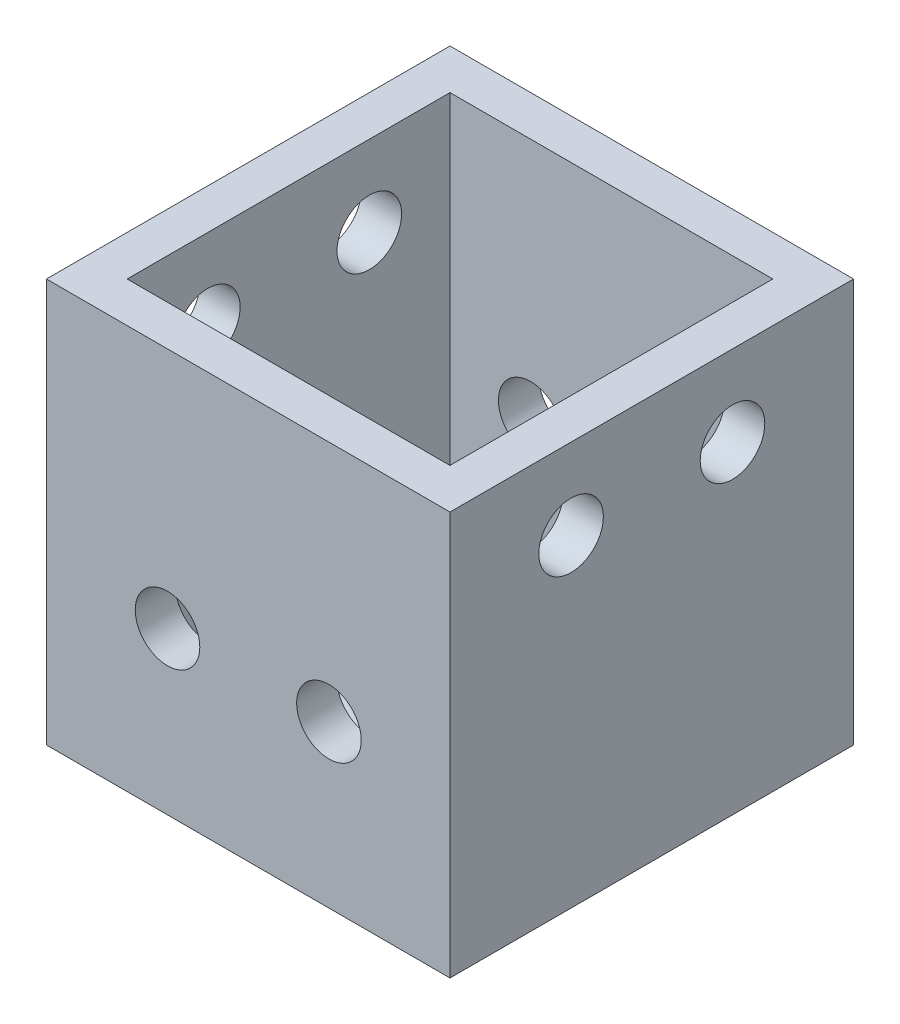
SolidWorks part; units mm, degrees
ref_plane "Front Plane" through (0, 0, 0) normal (0, 0, 1) x (1, 0, 0)
ref_plane "Top Plane" through (0, 0, 0) normal (0, 1, 0) x (1, 0, 0)
ref_plane "Right Plane" through (0, 0, 0) normal (1, 0, 0) x (0, 0, -1)
sketch "Sketch1" plane through (0, 0, 0) normal (0, 1, 0) x (1, 0, 0)
  line L1 (0, 0) -> (50, 0)
  line L2 (0, 0) -> (0, 50)
  line L3 (0, 50) -> (50, 50)
  line L4 (50, 0) -> (50, 50)
  dimension "D1" = 50
  dimension "D2" = 50
extrude "Boss-Extrude1" add sketch "Sketch1" along normal blind 50
sketch "Sketch2" plane through (0, 50, 0) normal (0, 1, 0) x (1, 0, 0)
  line L0 (50, 0) -> (50, 50) construction
  line L1 (5, 45) -> (45, 45)
  line L2 (5, 45) -> (5, 5)
  line L3 (5, 5) -> (45, 5)
  line L4 (45, 45) -> (45, 5)
  line L5 (0, 50) -> (0, 0) construction
  line L6 (0, 0) -> (50, 0) construction
  line L7 (50, 50) -> (0, 50) construction
  dimension "D1" = 5
  dimension "D2" = 5
  dimension "D3" = 5
  dimension "D4" = 5
extrude "Cut-Extrude1" cut sketch "Sketch2" against normal blind 45
sketch "Sketch3" plane through (0, 5, 0) normal (0, 1, 0) x (1, 0, 0)
  line L0 (45, 5) -> (45, 45) construction
  line L1 (5, 5) -> (45, 5) construction
  line L2 (5, 45) -> (5, 5) construction
  line L3 (45, 45) -> (5, 45) construction
  circle A0 centre (13, 37) radius 4
  circle A1 centre (37, 37) radius 4
  circle A2 centre (13, 13) radius 4
  circle A3 centre (37, 13) radius 4
  point P18 (-31.2434, 48.8756)
  dimension "D1" = 8
  dimension "D2" = 8
  dimension "D3" = 8
  dimension "D4" = 8
  dimension "D9" = 8
  dimension "D10" = 8
  dimension "D5" = 8
  dimension "D6" = 8
  dimension "D7" = 8
  dimension "D8" = 8
  dimension "D11" = 8
  dimension "D12" = 8
extrude "Cut-Extrude2" cut sketch "Sketch3" against normal blind 45
sketch "Sketch4" plane through (0, 0, 0) normal (0, 0, 1) x (1, 0, 0)
  line L0 (0, 0) -> (50, 0) construction
  line L1 (0, 50) -> (0, 0) construction
  line L2 (50, 50) -> (50, 0) construction
  circle A0 centre (15, 20) radius 4
  circle A1 centre (35, 20) radius 4
  dimension "D1" = 8
  dimension "D2" = 8
  dimension "D6" = 15
  dimension "D3" = 20
  dimension "D4" = 20
  dimension "D5" = 15
extrude "Cut-Extrude3" cut sketch "Sketch4" against normal through all both and the other way through all
sketch "Sketch5" plane through (50, 0, 0) normal (1, 0, 0) x (0, 0, -1)
  line L0 (50, 50) -> (50, 0) construction
  line L1 (0, 50) -> (0, 0) construction
  line L2 (0, 0) -> (50, 0) construction
  circle A0 centre (15, 40) radius 4
  circle A1 centre (35, 40) radius 4
  dimension "D1" = 8
  dimension "D2" = 8
  dimension "D6" = 40
  dimension "D3" = 15
  dimension "D4" = 15
  dimension "D5" = 40
extrude "Cut-Extrude4" cut sketch "Sketch5" against normal through all both and the other way through all
